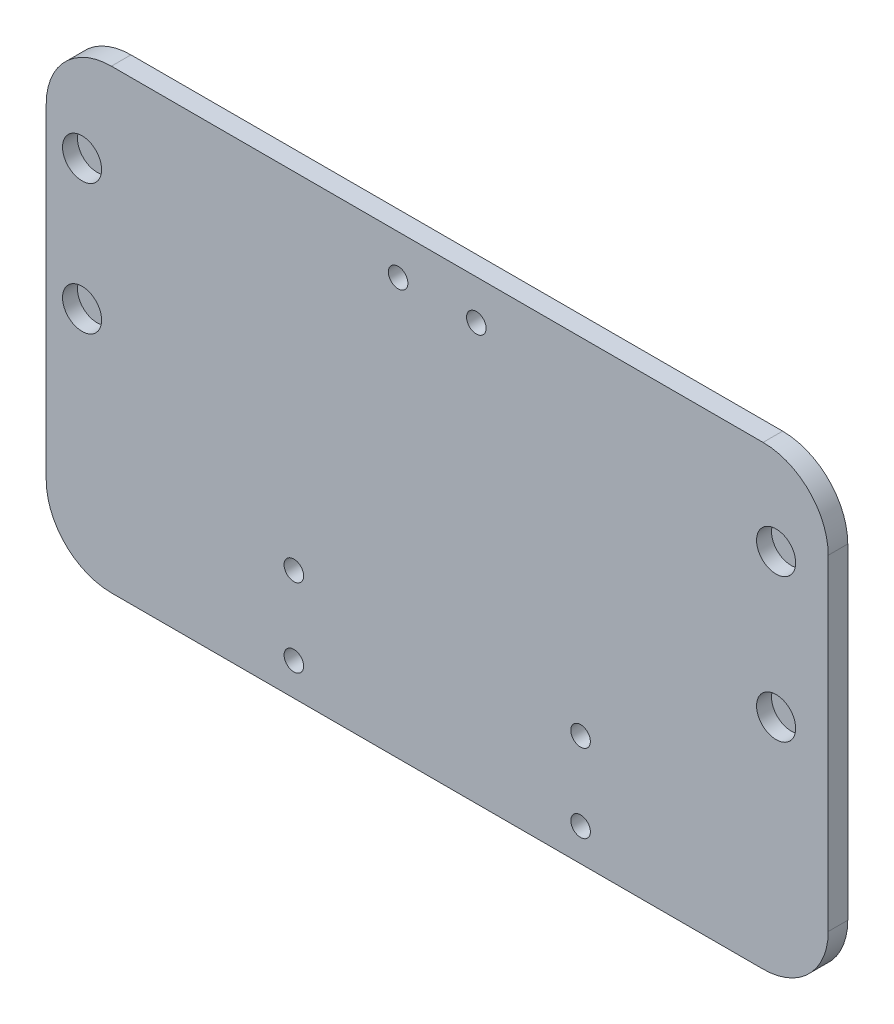
SolidWorks part; units mm, degrees
ref_plane "Front Plane" through (0, 0, 0) normal (0, 0, 1) x (1, 0, 0)
ref_plane "Top Plane" through (0, 0, 0) normal (0, 1, 0) x (1, 0, 0)
ref_plane "Right Plane" through (0, 0, 0) normal (1, 0, 0) x (0, 0, -1)
sketch "Sketch1" plane through (0, 0, 0) normal (0, 0, 1) x (1, 0, 0)
  line L1 (-98.4549, 37.7039) -> (1.5451, 37.7039)
  line L2 (-108.4549, 27.7039) -> (-108.4549, -22.2961)
  line L3 (-98.4549, -32.2961) -> (1.5451, -32.2961)
  line L4 (11.5451, 27.7039) -> (11.5451, -22.2961)
  arc A0 (1.5451, 37.7039) -> (11.5451, 27.7039) centre (1.5451, 27.7039) cw
  arc A1 (1.5451, -32.2961) -> (11.5451, -22.2961) centre (1.5451, -22.2961) ccw
  arc A2 (-108.4549, -22.2961) -> (-98.4549, -32.2961) centre (-98.4549, -22.2961) ccw
  arc A3 (-98.4549, 37.7039) -> (-108.4549, 27.7039) centre (-98.4549, 27.7039) ccw
  point P4 (0, 0)
  point P7 (11.5451, 37.7039)
  point P12 (-108.4549, -32.2961)
  point P15 (-108.4549, 37.7039)
  dimension "D3" = 10
  dimension "D1" = 70
  dimension "D2" = 120
extrude "Boss-Extrude1" add sketch "Sketch1" along normal blind 3
sketch "Sketch2" plane through (0, 0, 3) normal (0, 0, 1) x (1, 0, 0)
  line L0 (-108.4549, 27.7039) -> (-108.4549, -22.2961) construction
  line L1 (-98.4549, -32.2961) -> (1.5451, -32.2961) construction
  line L3 (-108.4549, 27.7039) -> (-108.4549, -22.2961) construction
  circle A0 centre (-54.4549, 31.6066) radius 1.5
  circle A1 centre (-42.4549, 31.6066) radius 1.5
  circle A2 centre (-70.4549, -15.2961) radius 1.5
  circle A3 centre (-70.4549, -27.2961) radius 1.5
  circle A4 centre (-26.4549, -15.2961) radius 1.5
  circle A5 centre (-26.4549, -27.2961) radius 1.5
  dimension "D1" = 12
  dimension "D2" = 12
  dimension "D3" = 12
  dimension "D5" = 38
  dimension "D6" = 54
  dimension "D7" = 5
  dimension "D4" = 44
extrude "Cut-Extrude1" cut sketch "Sketch2" against normal through all
sketch "Sketch3" plane through (0, 0, 3) normal (0, 0, 1) x (1, 0, 0)
  line L0 (1.5451, 37.7039) -> (-98.4549, 37.7039) construction
  line L1 (-108.4549, 27.7039) -> (-108.4549, -22.2961) construction
  circle A0 centre (-102.9549, 23.2039) radius 3
  circle A1 centre (-102.9549, 3.2039) radius 3
  circle A2 centre (3.5451, 24.2039) radius 3
  circle A3 centre (3.5451, 2.2039) radius 3
  dimension "D1" = 20
  dimension "D2" = 106.5
  dimension "D3" = 14.5
  dimension "D4" = 13.5
  dimension "D5" = 5.5
  dimension "D6" = 22
  dimension "D7" = 106.5
extrude "Cut-Extrude2" cut sketch "Sketch3" against normal blind 2.3
